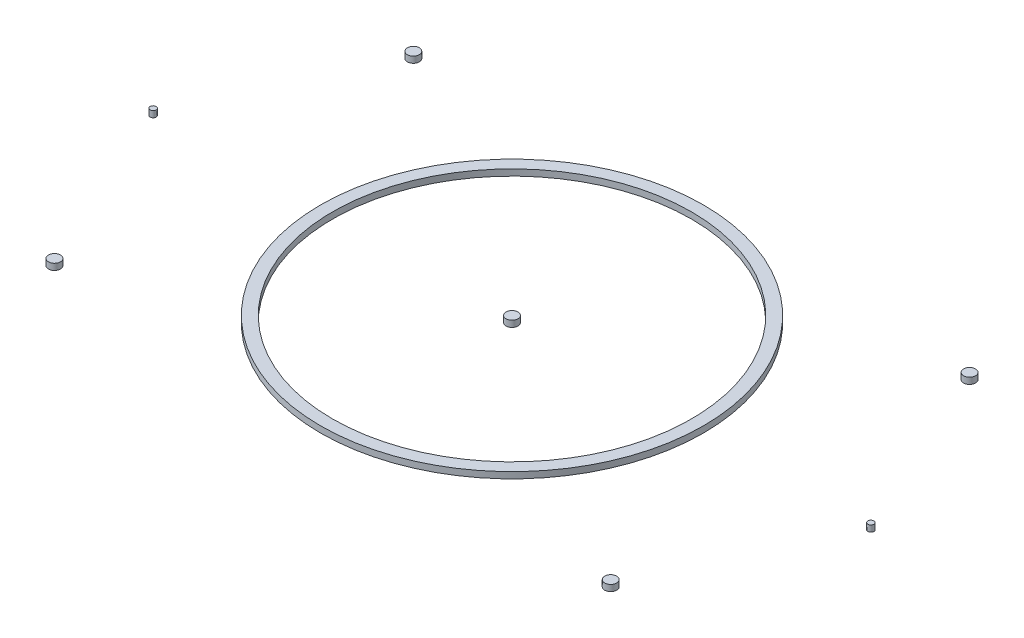
SolidWorks part; units mm, degrees
ref_plane "Спереди" through (0, 0, 0) normal (0, 0, 1) x (1, 0, 0)
ref_plane "Сверху" through (0, 0, 0) normal (0, 1, 0) x (1, 0, 0)
ref_plane "Справа" through (0, 0, 0) normal (1, 0, 0) x (0, 0, -1)
ref_plane "Плоскость4"
sketch "Эскиз1" plane through (0, 0, 0) normal (0, 1, 0) x (-1, 0, 0)
  circle A0 centre (-465, -300) radius 10
  circle A1 centre (-465, 300) radius 10
  circle A2 centre (465, 300) radius 10
  circle A3 centre (0, 0) radius 320
  circle A4 centre (0, 0) radius 300
  circle A5 centre (465, -300) radius 10
  circle A6 centre (0, 0) radius 10
  circle A7 centre (-600, 0) radius 5
  circle A8 centre (600, 0) radius 5
  dimension "D1" = 600
  dimension "D2" = 20
  dimension "D3" = 10
  dimension "D4" = 1106.447
extrude "Выдавливание1" add sketch "Эскиз1" along normal blind 10.5 contours A0 | A1 | A2 | A6 | A5 | A7 | A8 | A3 A4
